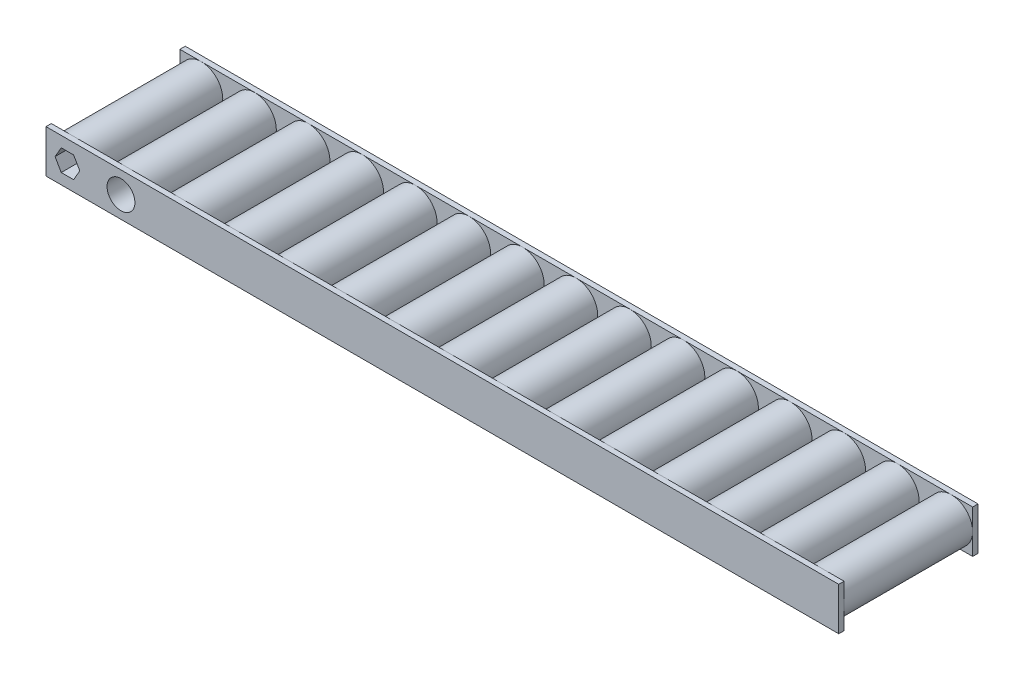
SolidWorks part; units mm, degrees
ref_plane "Front Plane" through (0, 0, 0) normal (0, 0, 1) x (1, 0, 0)
ref_plane "Top Plane" through (0, 0, 0) normal (0, 1, 0) x (1, 0, 0)
ref_plane "Right Plane" through (0, 0, 0) normal (1, 0, 0) x (0, 0, -1)
sketch "Sketch1" plane through (0, 0, 0) normal (0, 0, 1) x (1, 0, 0)
  circle A0 centre (0, 0) radius 12.7
  dimension "D1" = 25.4
extrude "Boss-Extrude1" add sketch "Sketch1" along normal blind 76.2 contours A0
pattern_linear "LPattern1" count 15 spacing 31.75 along (1, 0, 0) of "Boss-Extrude1"
sketch "Sketch2" plane through (0, 0, 76.2) normal (0, 0, 1) x (1, 0, 0)
  line L0 (-12.7, 12.7) -> (-12.7, -12.7)
  line L1 (-12.7, -12.7) -> (457.2, -12.7)
  line L2 (457.2, -12.7) -> (457.2, 12.7)
  line L3 (457.2, 12.7) -> (-12.7, 12.7)
  dimension "D1" = 469.9
  dimension "D2" = 25.4
extrude "Boss-Extrude2" add sketch "Sketch2" along normal blind 3.175
ref_plane "Plane1" through (0, 0, 38.1) normal (0, 0, 1) x (1, 0, 0)
mirror "Mirror1" about plane through (0, 0, 38.1) normal (0, 0, 1) of "Boss-Extrude2"
sketch "Sketch3" plane through (0, 0, 79.375) normal (0, 0, 1) x (1, 0, 0)
  line L1 (7.3323, 0) -> (3.6662, 6.35)
  line L2 (31.75, -12.7) -> (63.5, -12.7)
  line L3 (63.5, 12.7) -> (31.75, 12.7)
  line L6 (3.6662, 6.35) -> (-3.6662, 6.35)
  line L7 (-3.6662, 6.35) -> (-7.3323, 0)
  line L8 (-7.3323, 0) -> (-3.6662, -6.35)
  line L9 (-3.6662, -6.35) -> (3.6662, -6.35)
  line L10 (3.6662, -6.35) -> (7.3323, 0)
  arc A0 (0, 12.7) -> (-12.7, 0) centre (0, 0) ccw construction
  arc A1 (0, -12.7) -> (0, 12.7) centre (0, 0) ccw construction
  arc A2 (31.75, -12.7) -> (31.75, 12.7) centre (31.75, 0) ccw
  arc A3 (63.5, 12.7) -> (63.5, -12.7) centre (63.5, 0) ccw
  arc A4 (31.75, -12.7) -> (31.75, 12.7) centre (31.75, 0) ccw construction
  arc A6 (31.75, 12.7) -> (31.75, -12.7) centre (31.75, 0) ccw construction
  arc A7 (0, 12.7) -> (-12.7, 0) centre (0, 0) ccw construction
  arc A8 (0, -12.7) -> (0, 12.7) centre (0, 0) ccw construction
  arc A9 (31.75, 12.7) -> (31.75, -12.7) centre (31.75, 0) ccw construction
  circle A10 centre (31.75, 0) radius 8.255
  circle A11 centre (0, 0) radius 6.35 construction
  dimension "D2" = 16.51
  dimension "D3" = 12.7
  dimension "D1" = 0
extrude "Cut-Extrude1" cut sketch "Sketch3" against normal through all
